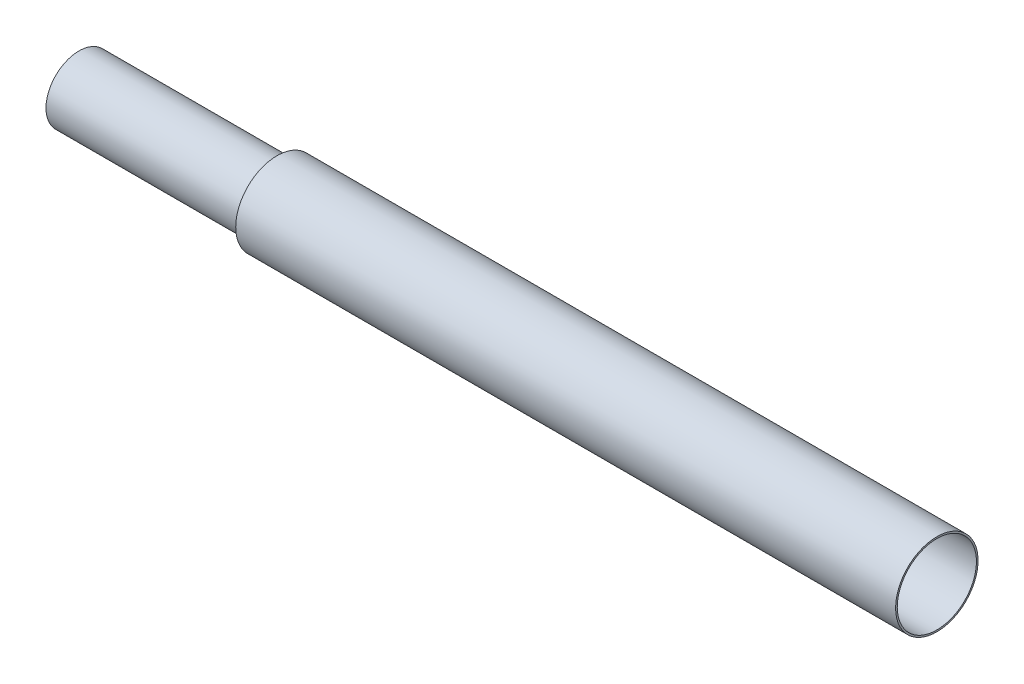
SolidWorks part; units mm, degrees
ref_plane "Front Plane" through (0, 0, 0) normal (0, 0, 1) x (1, 0, 0)
ref_plane "Top Plane" through (0, 0, 0) normal (0, 1, 0) x (1, 0, 0)
ref_plane "Right Plane" through (0, 0, 0) normal (1, 0, 0) x (0, 0, -1)
sketch "Sketch1" plane through (0, 0, 0) normal (0, 0, 1) x (1, 0, 0)
  line L0 (0, 200) -> (1200, 200)
  line L1 (1200, 200) -> (1200, 250)
  line L2 (1200, 250) -> (5200, 250)
  line L3 (0, 0) -> (252.847, 0) construction
  dimension "D1" = 4000
  dimension "D2" = 50
  dimension "D3" = 1200
  dimension "D4" = 200
revolve "Revolve-Thin1" add sketch "Sketch1" angle 360 about L3
